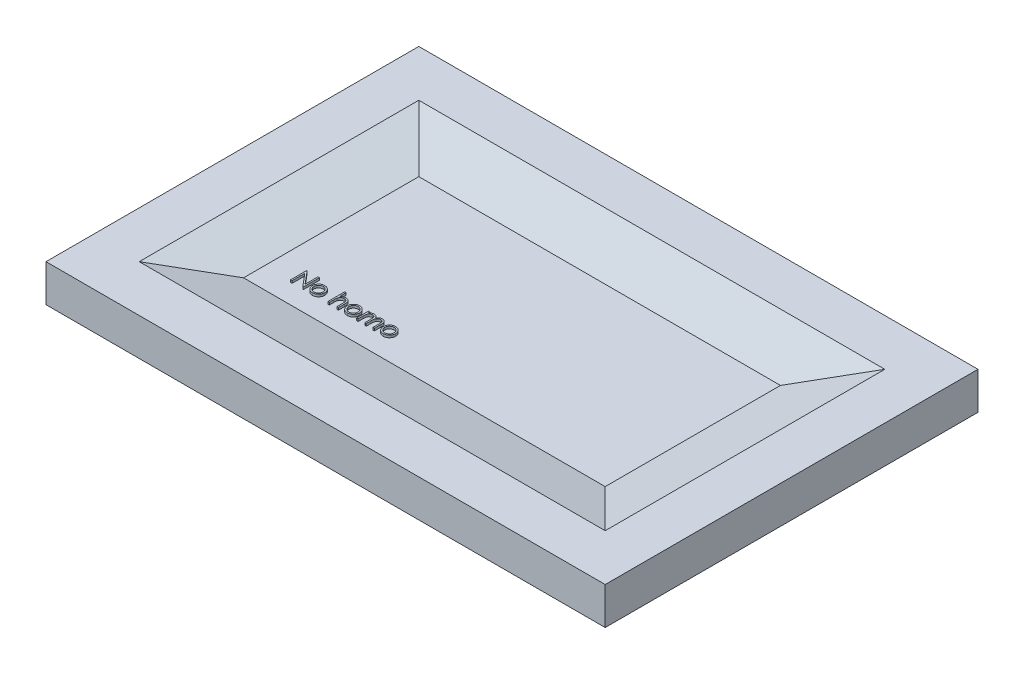
SolidWorks part; units mm, degrees
ref_plane "Front Plane" through (0, 0, 0) normal (0, 0, 1) x (1, 0, 0)
ref_plane "Top Plane" through (0, 0, 0) normal (0, 1, 0) x (1, 0, 0)
ref_plane "Right Plane" through (0, 0, 0) normal (1, 0, 0) x (0, 0, -1)
sketch "Sketch1" plane through (0, 0, 0) normal (0, 1, 0) x (1, 0, 0)
  line L1 (60, 40) -> (-60, 40)
  line L2 (60, 40) -> (60, -40)
  line L3 (60, -40) -> (-60, -40)
  line L4 (-60, 40) -> (-60, -40)
  line L5 (60, 40) -> (-60, -40) construction
  line L6 (60, -40) -> (-60, 40) construction
  point P0 (0, 0)
  dimension "D1" = 120
  dimension "D2" = 80
extrude "Boss-Extrude1" add sketch "Sketch1" along normal mid plane 8
sketch3d "3DSketch1"
  line L0 (-50, 4, 30) -> (50, 4, 30)
  line L1 (50, 4, 30) -> (50, 4, -30)
  line L2 (50, 4, -30) -> (-50, 4, -30)
  line L3 (-50, 4, -30) -> (-50, 4, 30)
  line L4 (-50, 4, 30) -> (50, 4, 30)
  line L5 (50, 4, 30) -> (50, 4, -30)
  line L6 (50, 4, -30) -> (-50, 4, -30)
  line L7 (-50, 4, -30) -> (-50, 4, 30)
  dimension "D1" = 10
extrude "Cut-Extrude1" cut sketch "3DSketch1" along direction (0, -1, 0) on the side against the normal blind 3 draft 75 contours L4 L5 L6 L7
mirror "Mirror1" about plane through (0, 0, 0) normal (0, 1, 0) of "Cut-Extrude1"
sketch "Sketch2" plane through (0, 1, 0) normal (0, 1, 0) x (1, 0, 0)
  line L0 (-33.334, -14.6374) -> (-8.334, -14.6374) construction
  text T0 "No homo"
  point P3 (0, 0)
  point P4 (0, 0)
  dimension "D1" = 25
extrude "Boss-Extrude3" add sketch "Sketch2" along normal blind 0.5
sketch "Sketch6" plane through (0, -1, 0) normal (0, -1, 0) x (1, 0, 0)
  line L0 (32.5485, 15.0411) -> (7.6344, 15.0411) construction
  text T0 "No homo"
extrude "Boss-Extrude6" add sketch "Sketch6" along normal blind 0.5
